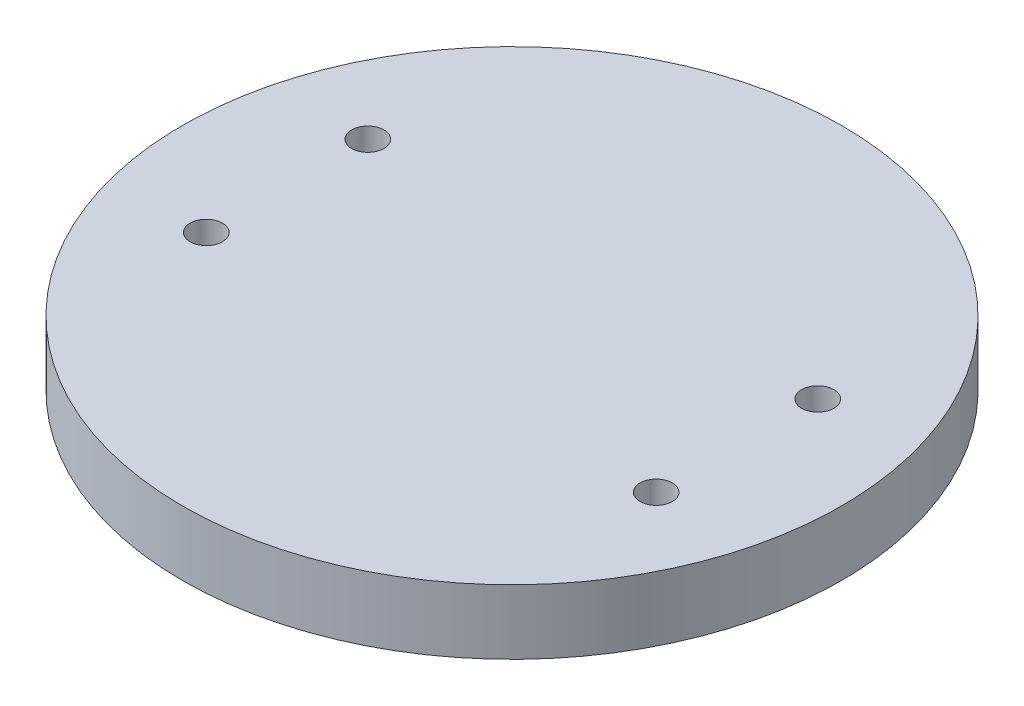
SolidWorks part; units mm, degrees
ref_plane "Front Plane" through (0, 0, 0) normal (0, 0, 1) x (1, 0, 0)
ref_plane "Top Plane" through (0, 0, 0) normal (0, 1, 0) x (1, 0, 0)
ref_plane "Right Plane" through (0, 0, 0) normal (1, 0, 0) x (0, 0, -1)
sketch "Sketch1" plane through (0, 0, 0) normal (0, 1, 0) x (1, 0, 0)
  circle A0 centre (0, 0) radius 64.77
  dimension "D1" = 129.54
extrude "Boss-Extrude1" add sketch "Sketch1" along normal blind 12.7
sketch "Sketch2" plane through (0, 12.7, 0) normal (0, 1, 0) x (1, 0, 0)
  line L0 (-72.7941, 0) -> (72.3878, 0) construction
  line L1 (0, 70.7385) -> (0, -72.4581) construction
  circle A0 centre (-44.2148, 15.875) radius 3.175
  circle A1 centre (-44.2148, -15.875) radius 3.175
  circle A2 centre (44.2148, -15.875) radius 3.175
  circle A3 centre (44.2148, 15.875) radius 3.175
  dimension "D1" = 6.35
  dimension "D2" = 15.875
extrude "Cut-Extrude1" cut sketch "Sketch2" against normal through all
